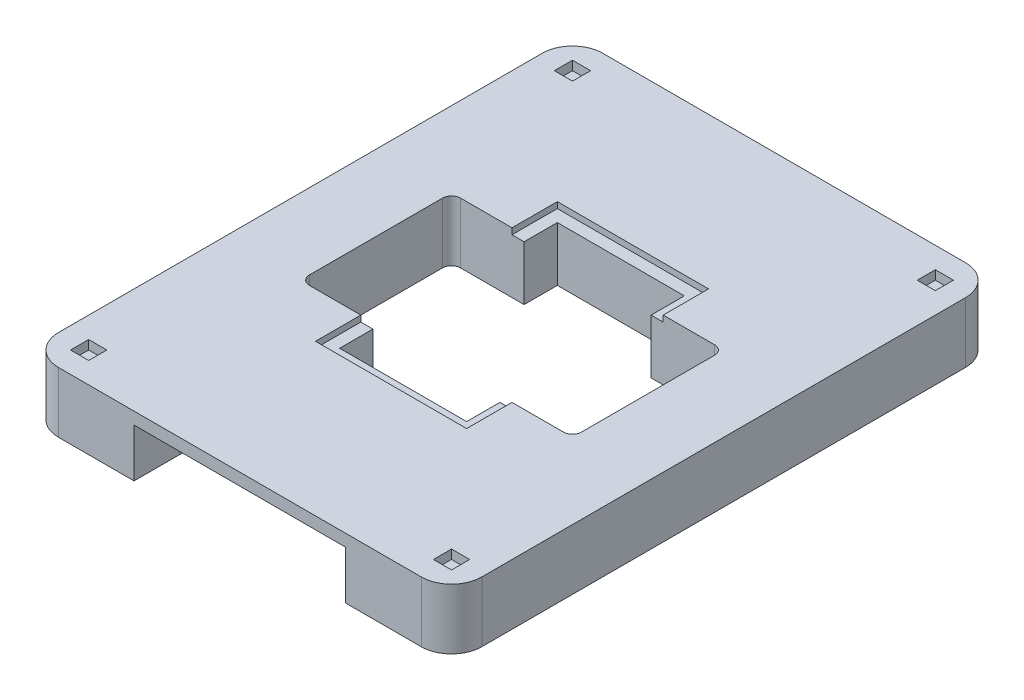
SolidWorks part; units mm, degrees
ref_plane "前视基准面" through (0, 0, 0) normal (0, 0, 1) x (1, 0, 0)
ref_plane "上视基准面" through (0, 0, 0) normal (0, 1, 0) x (1, 0, 0)
ref_plane "右视基准面" through (0, 0, 0) normal (1, 0, 0) x (0, 0, -1)
sketch "草图1" plane through (0, 0, 0) normal (0, 1, 0) x (1, 0, 0)
  line L1 (100, -100) -> (-100, -100)
  line L2 (100, -100) -> (100, 100)
  line L3 (100, 100) -> (-100, 100)
  line L4 (-100, -100) -> (-100, 100)
  line L5 (100, -100) -> (-100, 100) construction
  line L6 (100, 100) -> (-100, -100) construction
  point P1 (0, 0)
  dimension "D1" = 200
  dimension "D2" = 200
extrude "凸台-拉伸1" add sketch "草图1" along normal blind 20
sketch "草图2" plane through (0, 20, 0) normal (0, 1, 0) x (1, 0, 0)
  line L1 (70, -90) -> (-70, -90)
  line L2 (70, -90) -> (70, 90)
  line L3 (70, 90) -> (-70, 90)
  line L4 (-70, -90) -> (-70, 90)
  line L5 (70, -90) -> (-70, 90) construction
  line L6 (70, 90) -> (-70, -90) construction
  line L7 (100, -100) -> (-100, -100)
  line L8 (100, -100) -> (100, 100)
  line L9 (100, 100) -> (-100, 100)
  line L10 (-100, -100) -> (-100, 100)
  line L11 (100, -100) -> (-100, 100) construction
  line L12 (100, 100) -> (-100, -100) construction
  point P0 (0, 0)
  point P6 (0, 0)
  dimension "D1" = 140
  dimension "D2" = 180
extrude "切除-拉伸2" cut sketch "草图2" against normal through all
fillet "圆角1" radius 10 1 edges at (-70, 10, -90)
fillet "圆角2" radius 10 1 edges at (70, 10, -90)
fillet "圆角3" radius 10 1 edges at (70, 10, 90)
fillet "圆角4" radius 10 1 edges at (-70, 10, 90)
sketch "草图4" plane through (0, 0, 0) normal (0, -1, 0) x (1, 0, 0)
  line L5 (-60, 90) -> (60, 90) construction
  line L82 (-70, -80) -> (-70, 80) construction
  line L83 (-59.5, 84.9749) -> (-59.5, 86)
  line L95 (-59.5, 74) -> (-60.5, 74)
  line L97 (-59.5, 74) -> (-59.5, 75.0251)
  line L102 (-59.5, 86) -> (-60.5, 86)
  line L103 (-60.5, 74) -> (-60.5, 75.0251)
  line L108 (-66, 79.5) -> (-64.9749, 79.5)
  line L109 (-66, 79.5) -> (-66, 80.5)
  line L110 (-66, 80.5) -> (-64.9749, 80.5)
  line L111 (-54, 79.5) -> (-54, 80.5)
  line L115 (-60.5, 84.9749) -> (-60.5, 86)
  line L116 (-55.0251, 80.5) -> (-54, 80.5)
  line L120 (-55.0251, 79.5) -> (-54, 79.5)
  arc A5 (-60.5, 84.9749) -> (-64.9749, 80.5) centre (-60, 80) ccw
  arc A6 (-55.0251, 80.5) -> (-59.5, 84.9749) centre (-60, 80) ccw
  arc A7 (-59.5, 75.0251) -> (-55.0251, 79.5) centre (-60, 80) ccw
  arc A8 (-64.9749, 79.5) -> (-60.5, 75.0251) centre (-60, 80) ccw
  point P0 (0, 0)
  point P2 (-60, 80)
  dimension "D3" = 1
  dimension "D4" = 12
  dimension "D1" = 10
  dimension "D2" = 10
  dimension "D5" = 1
  dimension "D6" = 12
extrude "切除-拉伸4" cut sketch "草图4" against normal blind 5
mirror "镜向3" about plane through (0, 0, 0) normal (1, 0, 0) of "切除-拉伸4" second plane through (0, 0, 0) second plane normal (0, 0, 1)
sketch "草图5" plane through (0, 0, 0) normal (0, -1, 0) x (1, 0, 0)
  line L1 (60, -80) -> (-60, -80) construction
  line L2 (60, -80) -> (60, 80) construction
  line L3 (60, 80) -> (-60, 80) construction
  line L4 (-60, -80) -> (-60, 80) construction
  line L5 (60, -80) -> (-60, 80) construction
  line L6 (60, 80) -> (-60, -80) construction
  circle A0 centre (-60, 80) radius 5
  point P0 (0, 0)
  dimension "D3" = 10
  dimension "D1" = 120
  dimension "D2" = 160
extrude "切除-拉伸5" cut sketch "草图5" against normal blind 6.2
sketch "草图7" plane through (0, 0, 0) normal (0, -1, 0) x (1, 0, 0)
  line L0 (-60, 90) -> (60, 90) construction
  line L1 (35, 110) -> (-35, 110)
  line L2 (35, 110) -> (35, 75)
  line L3 (30, 70) -> (-30, 70)
  line L4 (-35, 110) -> (-35, 75)
  line L5 (35, 110) -> (-35, 70) construction
  line L6 (35, 70) -> (-35, 110) construction
  arc A0 (-30, 70) -> (-35, 75) centre (-30, 75) cw
  arc A1 (30, 70) -> (35, 75) centre (30, 75) ccw
  point P0 (0, 90)
  dimension "D3" = 5
  dimension "D4" = 5
  dimension "D1" = 70
  dimension "D2" = 40
extrude "切除-拉伸7" cut sketch "草图7" against normal blind 16
mirror "镜向6" about plane through (0, 0, 0) normal (0, 0, 1) of "切除-拉伸7"
sketch "草图8" plane through (0, 0, 0) normal (0, -1, 0) x (1, 0, 0)
  line L5 (40.5, -40.5) -> (-40.5, -40.5) construction
  line L6 (40.5, -40.5) -> (40.5, 40.5) construction
  line L7 (40.5, 40.5) -> (-40.5, 40.5) construction
  line L8 (-40.5, -40.5) -> (-40.5, 40.5) construction
  line L9 (40.5, -40.5) -> (-40.5, 40.5) construction
  line L10 (40.5, 40.5) -> (-40.5, -40.5) construction
  circle A4 centre (-40.5, 40.5) radius 4.1
  point P0 (0, 0)
  dimension "D1" = 81
  dimension "D2" = 81
extrude "切除-拉伸8" cut sketch "草图8" against normal blind 4
draft "拔模2" type of draft neutral plane draft angle 10 faces to draft 1 face at (-40.5, 4, 36.4) neutral plane through (-40.5, 4, 40.5) neutral plane normal (0, -1, 0) parameters "D1"=10
mirror "镜向10" about plane through (0, 0, 0) normal (1, 0, 0) of "拔模2", "切除-拉伸8"
mirror "镜向11" about plane through (0, 0, 0) normal (0, 0, 1) of "切除-拉伸8", "拔模2"
sketch "草图14" plane through (0, 20, 0) normal (0, 1, 0) x (1, 0, 0)
  line L1 (60, -80) -> (-60, -80) construction
  line L2 (60, -80) -> (60, 80) construction
  line L3 (60, 80) -> (-60, 80) construction
  line L4 (-60, -80) -> (-60, 80) construction
  line L5 (60, -80) -> (-60, 80) construction
  line L6 (60, 80) -> (-60, -80) construction
  line L7 (-57, 77) -> (-63, 77)
  line L8 (-57, 77) -> (-57, 83)
  line L9 (-57, 83) -> (-63, 83)
  line L10 (-63, 77) -> (-63, 83)
  line L11 (-57, 77) -> (-63, 83) construction
  line L12 (-57, 83) -> (-63, 77) construction
  point P0 (0, 0)
  dimension "D1" = 120
  dimension "D2" = 160
  dimension "D3" = 6
  dimension "D4" = 6
extrude "切除-拉伸9" cut sketch "草图14" against normal blind 3
mirror "镜向12" about plane through (0, 0, 0) normal (1, 0, 0) of "切除-拉伸9" second plane through (0, 0, 0) second plane normal (0, 0, 1)
sketch "草图15" plane through (0, 20, 0) normal (0, 1, 0) x (1, 0, 0)
  line L1 (25, -40) -> (-25, -40)
  line L2 (25, -40) -> (25, 40)
  line L3 (25, 40) -> (-25, 40)
  line L4 (-25, -40) -> (-25, 40)
  line L5 (25, -40) -> (-25, 40) construction
  line L6 (25, 40) -> (-25, -40) construction
  point P0 (0, 0)
  dimension "D1" = 80
  dimension "D2" = 50
extrude "切除-拉伸10" cut sketch "草图15" against normal blind 2
sketch "草图16" plane through (0, 18, 0) normal (0, 1, 0) x (1, 0, 0)
  line L1 (21, -36) -> (-21, -36)
  line L2 (21, -36) -> (21, 36)
  line L3 (21, 36) -> (-21, 36)
  line L4 (-21, -36) -> (-21, 36)
  line L5 (21, -36) -> (-21, 36) construction
  line L6 (21, 36) -> (-21, -36) construction
  point P0 (0, 0)
  dimension "D1" = 42
  dimension "D2" = 72
extrude "切除-拉伸11" cut sketch "草图16" against normal through all
sketch "草图17" plane through (0, 20, 0) normal (0, 1, 0) x (1, 0, 0)
  line L1 (42, -25) -> (-42, -25)
  line L2 (45, -22) -> (45, 22)
  line L3 (42, 25) -> (-42, 25)
  line L4 (-45, -22) -> (-45, 22)
  line L5 (45, -25) -> (-45, 25) construction
  line L6 (45, 25) -> (-45, -25) construction
  arc A0 (45, -22) -> (42, -25) centre (42, -22) cw
  arc A1 (45, 22) -> (42, 25) centre (42, 22) ccw
  arc A2 (-42, -25) -> (-45, -22) centre (-42, -22) cw
  arc A3 (-45, 22) -> (-42, 25) centre (-42, 22) cw
  point P0 (0, 0)
  dimension "D3" = 3
  dimension "D1" = 50
  dimension "D2" = 90
extrude "切除-拉伸12" cut sketch "草图17" against normal through all
